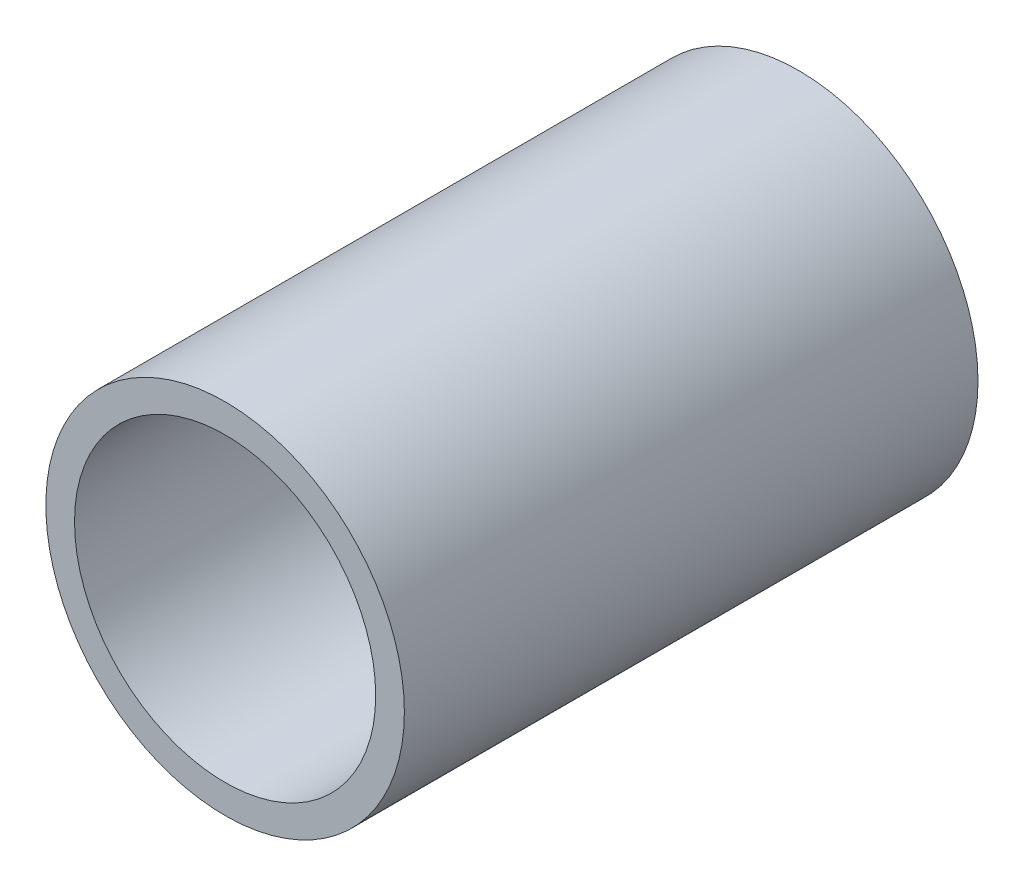
SolidWorks part; units mm, degrees
ref_plane "正面" through (0, 0, 0) normal (0, 0, 1) x (1, 0, 0)
ref_plane "平面" through (0, 0, 0) normal (0, 1, 0) x (1, 0, 0)
ref_plane "右側面" through (0, 0, 0) normal (1, 0, 0) x (0, 0, -1)
sketch "ｽｹｯﾁ1" plane through (0, 0, 0) normal (0, 0, 1) x (1, 0, 0)
  circle A0 centre (0, 0) radius 3.75
  circle A1 centre (0, 0) radius 3.15
  dimension "D1" = 6.3
  dimension "D2" = 7.5
extrude "ﾎﾞｽ - 押し出し1" add sketch "ｽｹｯﾁ1" along normal blind 12
